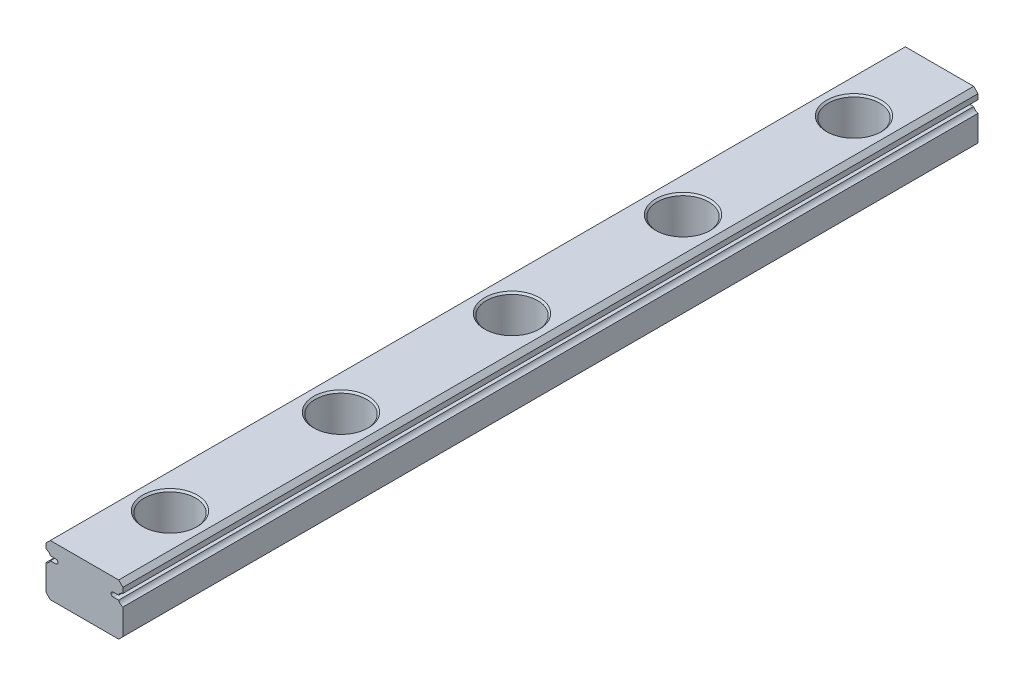
SolidWorks part; units mm, degrees
material "Chrome Stainless Steel"
ref_plane "Front Plane" through (0, 0, 0) normal (0, 0, 1) x (1, 0, 0)
ref_plane "Top Plane" through (0, 0, 0) normal (0, 1, 0) x (1, 0, 0)
ref_plane "Right Plane" through (0, 0, 0) normal (1, 0, 0) x (0, 0, -1)
sketch "Sketch1" plane through (0, 0, 0) normal (0, 0, 1) x (1, 0, 0)
  line L0 (0, 3) -> (0, -3) construction
  line L1 (4, -3) -> (-4, -3)
  line L2 (-4, -3) -> (-4.5, -2.5)
  line L3 (-4.5, -2.5) -> (-4.5, 0.5147)
  line L4 (4, 3) -> (-4, 3)
  line L5 (-4, 3) -> (-4.5, 2.5)
  line L6 (-4.5, 1.8853) -> (-4.5, 2.5)
  line L7 (-3.9889, 0.95) -> (-3.35, 0.95)
  line L8 (-3.9889, 1.45) -> (-3.35, 1.45)
  line L9 (3.9889, 0.95) -> (3.35, 0.95)
  line L10 (4, 3) -> (4.5, 2.5)
  line L11 (4.5, 1.8853) -> (4.5, 2.5)
  line L12 (3.9889, 1.45) -> (3.35, 1.45)
  line L13 (4.5, -2.5) -> (4.5, 0.5147)
  line L14 (4, -3) -> (4.5, -2.5)
  line L15 (-4.6427, 1.2) -> (-3.35, 1.2) construction
  line L16 (-3.6695, 1.45) -> (-3.6695, 0.95) construction
  line L17 (-3.1, 1.2) -> (-3.1, 1.5) construction
  arc A0 (-4.3532, 0.5627) -> (-4.5, 1.8853) centre (-4.6427, 1.2) ccw construction
  circle A1 centre (-3.35, 1.2) radius 0.25 construction
  arc A2 (-4.5, 0.5147) -> (-3.9889, 0.95) centre (-4.6427, 1.2) ccw
  arc A3 (-3.9889, 1.45) -> (-4.5, 1.8853) centre (-4.6427, 1.2) ccw
  arc A4 (-3.35, 0.95) -> (-3.35, 1.45) centre (-3.35, 1.2) ccw
  arc A5 (3.9889, 1.45) -> (4.5, 1.8853) centre (4.6427, 1.2) cw
  arc A6 (3.35, 0.95) -> (3.35, 1.45) centre (3.35, 1.2) cw
  arc A7 (4.5, 0.5147) -> (3.9889, 0.95) centre (4.6427, 1.2) cw
  point P4 (0, 0)
  point P9 (0, 0)
  point P18 (0, 0)
  point P33 (-4.677, 1.2)
  point P37 (-4.7996, 1.2)
  point P38 (-4.5554, 1.2)
  point P39 (-4.6392, 1.2)
  point P40 (0, 0)
  point P41 (-4.6427, 1.2)
  dimension "D5" = 4.2
  dimension "D6" = 0.7
  dimension "D7" = 0.25
  dimension "D10" = 1.4
  dimension "D1" = 6
  dimension "D2" = 0.5
  dimension "D3" = 0.5
  dimension "D4" = 4.5
  dimension "D8" = 0.5
  dimension "D9" = 0.5
extrude "Boss-Extrude1" add sketch "Sketch1" along normal blind 100 contours L13 A7 L9 A6 L12 A5 L11 L10 L4 L5 L6 A3 L8 A4 L7 A2 L3 L2 L1 L14
sketch "Sketch2" plane through (0, 3, 0) normal (0, 1, 0) x (1, 0, 0)
  line L1 (0, 0) -> (0, -10) construction
  line L2 (4, 0) -> (-4, 0) construction
  circle A0 centre (0, -10) radius 3
  dimension "D1" = 10
  dimension "D2" = 6
extrude "Cut-Extrude1" cut sketch "Sketch2" against normal blind 4.5
sketch "Sketch3" plane through (0, -1.5, 0) normal (0, 1, 0) x (1, 0, 0)
  circle A0 centre (0, -10) radius 1.75
  dimension "D1" = 3.5
extrude "Cut-Extrude2" cut sketch "Sketch3" against normal through all
chamfer "Chamfer1" distance 0.2 angle 45 2 edges at (-1.75, -3, 10) (-3, 3, 10)
pattern_linear "LPattern1" count 5 spacing 20 along (0, 0, 1) of "Cut-Extrude1", "Cut-Extrude2", "Chamfer1"
